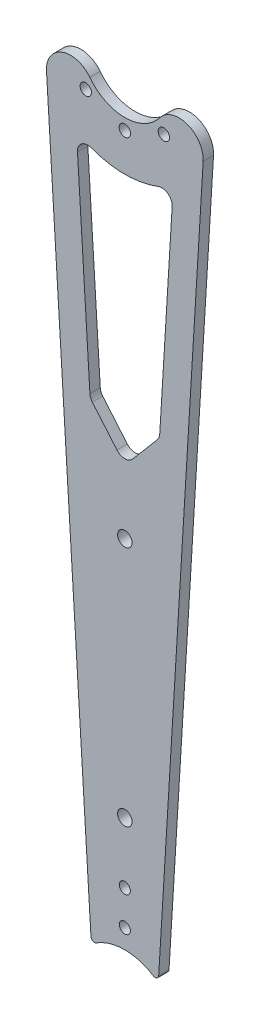
SolidWorks part; units mm, degrees
ref_plane "前视基准面" through (0, 0, 0) normal (0, 0, 1) x (1, 0, 0)
ref_plane "上视基准面" through (0, 0, 0) normal (0, 1, 0) x (1, 0, 0)
ref_plane "右视基准面" through (0, 0, 0) normal (1, 0, 0) x (0, 0, -1)
other "Configuration Table"
sketch "草图1" plane through (0, 0, 0) normal (0, 0, 1) x (1, 0, 0)
  line L0 (0, 0) -> (0, -21.9886) construction
  line L1 (0, 0) -> (-15.3152, -15.3152) construction
  line L2 (0, 0) -> (17.1443, -17.1443) construction
  line L3 (0, 50.5605) -> (0, -381.1612) construction
  line L4 (0, 0) -> (-15.4548, -4.1411) construction
  line L5 (10, -220) -> (-10, -220)
  line L6 (-10, -220) -> (-22.6976, -12.3955)
  line L8 (10, -220) -> (22.6976, -12.3955)
  circle A0 centre (0, 0) radius 16 construction
  circle A1 centre (0, 0) radius 12.75
  circle A2 centre (-11.3137, -11.3137) radius 1.65
  circle A3 centre (0, -16) radius 1.65
  circle A4 centre (11.3137, -11.3137) radius 1.65
  arc A6 (-10.1423, -7.7263) -> (-22.6976, -12.3955) centre (-15.7107, -11.9682) ccw
  arc A7 (10.1423, -7.7263) -> (22.6976, -12.3955) centre (15.7107, -11.9682) cw
  point P15 (0, -220)
  point P22 (0, -220)
  dimension "D1" = 32
  dimension "D2" = 25.5
  dimension "D5" = 3.3
  dimension "D6" = 3.3
  dimension "D7" = 3.3
  dimension "D12" = 14
  dimension "D3" = 45
  dimension "D4" = 45
  dimension "D8" = 220
  dimension "D9" = 75
  dimension "D10" = 10
  dimension "D11" = 3.5
extrude "凸台-拉伸1" add sketch "草图1" along normal blind 3
sketch "草图2" plane through (0, 0, 3) normal (0, 0, 1) x (1, 0, 0)
  line L0 (0, -227.7236) -> (0, -87.6518) construction
  line L1 (10, -220) -> (-10, -220) construction
  circle A0 centre (0, -216) radius 1.6
  circle A1 centre (0, -206) radius 1.6
  dimension "D1" = 4
  dimension "D2" = 10
  dimension "D3" = 3.2
  dimension "D4" = 3.2
extrude "切除-拉伸1" cut sketch "草图2" against normal blind 15
sketch "草图4" plane through (0, 0, 0) normal (0, 0, -1) x (-1, 0, 0)
  line L0 (-13.7159, -28.2019) -> (-10.1137, -87.0977)
  line L1 (-10, -220) -> (-22.6976, -12.3955) construction
  line L2 (0, 41.4898) -> (0, 27) construction
  line L3 (2.2925, -97.284) -> (9.4118, -88.8496)
  line L4 (0, -27) -> (0, -178.2536) construction
  line L5 (-2.2925, -97.284) -> (-9.4118, -88.8496)
  line L6 (13.7159, -28.2019) -> (10.1137, -87.0977)
  arc A0 (-9.6494, -25.2169) -> (9.6494, -25.2169) centre (0, 0) ccw
  arc A1 (13.7159, -28.2019) -> (9.6494, -25.2169) centre (10.7215, -28.0187) ccw
  arc A2 (-13.7159, -28.2019) -> (-9.6494, -25.2169) centre (-10.7215, -28.0187) cw
  arc A3 (9.4118, -88.8496) -> (10.1137, -87.0977) centre (7.1193, -86.9146) ccw
  arc A4 (2.2925, -97.284) -> (-2.2925, -97.284) centre (0, -95.349) cw
  arc A5 (-10.1137, -87.0977) -> (-9.4118, -88.8496) centre (-7.1193, -86.9146) ccw
  point P15 (14.0299, -23.0686)
  point P18 (-14.0299, -23.0686)
  point P22 (10.053, -88.09)
  point P25 (0, -100)
  point P28 (-10.053, -88.09)
  dimension "D2" = 54
  dimension "D3" = 3
  dimension "D6" = 3
  dimension "D1" = 8
  dimension "D4" = 100
  dimension "D5" = 60
extrude "切除-拉伸2" cut sketch "草图4" against normal blind 15
sketch "草图5" plane through (0, 0, 3) normal (0, 0, 1) x (1, 0, 0)
  line L0 (-12.2411, -94.7997) -> (-2.2925, -106.5861) construction
  line L1 (-9.4118, -88.8496) -> (-2.2925, -97.284) construction
  line L2 (-10, -220) -> (-22.6976, -12.3955) construction
  line L3 (-8.4988, -198.4027) -> (8.4988, -198.4027) construction
  line L4 (-17.528, -96.9179) -> (-11.4932, -195.5858) construction
  line L6 (17.528, -96.9179) -> (11.4932, -195.5858) construction
  line L7 (12.2411, -94.7997) -> (2.2925, -106.5861) construction
  line L8 (0, -107.651) -> (0, -201.1469) construction
  circle A0 centre (0, -188.4027) radius 2.1
  arc A1 (11.4932, -195.5858) -> (8.4988, -198.4027) centre (8.4988, -195.4027) cw construction
  arc A2 (-8.4988, -198.4027) -> (-11.4932, -195.5858) centre (-8.4988, -195.4027) cw construction
  arc A3 (2.2925, -106.5861) -> (-2.2925, -106.5861) centre (0, -104.651) cw construction
  arc A4 (17.528, -96.9179) -> (12.2411, -94.7997) centre (14.5336, -96.7348) ccw construction
  arc A5 (-12.2411, -94.7997) -> (-17.528, -96.9179) centre (-14.5336, -96.7348) ccw construction
  circle A6 centre (0, -118.4027) radius 2.1
  point P12 (-11.3209, -198.4027)
  point P23 (-18.0807, -87.8814)
  dimension "D2" = 3
  dimension "D3" = 4.2
  dimension "D4" = 4.2
  dimension "D5" = 10
  dimension "D6" = 70
  dimension "D1" = 6
extrude "切除-拉伸4" cut sketch "草图5" against normal blind 10
sketch "草图3" plane through (0, 0, 3) normal (0, 0, 1) x (1, 0, 0)
  line L0 (-10, -220) -> (-9.806, -223.1719)
  line L3 (0, -220) -> (0, -221.5633) construction
  line L5 (10, -220) -> (9.806, -223.1719)
  line L6 (-10, -220) -> (-22.6976, -12.3955) construction
  line L10 (-22.6976, -12.3955) -> (-10, -220)
  line L11 (-10, -220) -> (10, -220)
  line L12 (10, -220) -> (22.6976, -12.3955)
  line L13 (-22.6976, -12.3955) -> (-10, -220)
  line L14 (-10, -220) -> (10, -220)
  line L15 (10, -220) -> (22.6976, -12.3955)
  arc A0 (8.2741, -223.9564) -> (-8.2741, -223.9564) centre (0, -237.0633) ccw
  arc A1 (-9.806, -223.1719) -> (-8.2741, -223.9564) centre (-8.8079, -223.1108) ccw
  arc A2 (9.806, -223.1719) -> (8.2741, -223.9564) centre (8.8079, -223.1108) cw
  arc A6 (22.6976, -12.3955) -> (10.1423, -7.7263) centre (15.7107, -11.9682) ccw
  arc A7 (-10.1423, -7.7263) -> (10.1423, -7.7263) centre (0, 0) ccw
  arc A8 (-10.1423, -7.7263) -> (-22.6976, -12.3955) centre (-15.7107, -11.9682) ccw
  arc A9 (22.6976, -12.3955) -> (10.1423, -7.7263) centre (15.7107, -11.9682) ccw
  arc A10 (-10.1423, -7.7263) -> (10.1423, -7.7263) centre (0, 0) ccw
  arc A11 (-10.1423, -7.7263) -> (-22.6976, -12.3955) centre (-15.7107, -11.9682) ccw
  line M10 (-10, -220) -> (10, -220)
  dimension "D1" = 31
  dimension "D2" = 2
  dimension "D3" = 3.1778
  dimension "D4" = 0
extrude "凸台-拉伸2" add sketch "草图3" against normal blind 3 contours L14 L3 A0 A2 L5 | L3 L0 A1 A0 M10
sketch "草图6" plane through (0, 0, 3) normal (0, 0, 1) x (1, 0, 0)
  line L0 (-11.6446, -193.1108) -> (11.6446, -193.1108)
  line L2 (-22.6976, -12.3955) -> (-9.806, -223.1719)
  line L3 (9.806, -223.1719) -> (22.6976, -12.3955)
  line L4 (-22.6976, -12.3955) -> (-9.806, -223.1719)
  line L5 (9.806, -223.1719) -> (22.6976, -12.3955)
  circle A0 centre (0, -216) radius 1.6 construction
  circle A1 centre (0, -216) radius 1.6
  circle A2 centre (0, -206) radius 1.6 construction
  circle A3 centre (0, -206) radius 1.6
  arc A6 (22.6976, -12.3955) -> (10.1423, -7.7263) centre (15.7107, -11.9682) ccw
  arc A7 (-10.1423, -7.7263) -> (10.1423, -7.7263) centre (0, 0) ccw
  arc A8 (-10.1423, -7.7263) -> (-22.6976, -12.3955) centre (-15.7107, -11.9682) ccw
  arc A9 (-9.806, -223.1719) -> (-8.2741, -223.9564) centre (-8.8079, -223.1108) ccw
  arc A10 (8.2741, -223.9564) -> (-8.2741, -223.9564) centre (0, -237.0633) ccw
  arc A11 (8.2741, -223.9564) -> (9.806, -223.1719) centre (8.8079, -223.1108) ccw
  arc A12 (22.6976, -12.3955) -> (10.1423, -7.7263) centre (15.7107, -11.9682) ccw
  arc A13 (-10.1423, -7.7263) -> (10.1423, -7.7263) centre (0, 0) ccw
  arc A14 (-10.1423, -7.7263) -> (-22.6976, -12.3955) centre (-15.7107, -11.9682) ccw
  arc A15 (-9.806, -223.1719) -> (-8.2741, -223.9564) centre (-8.8079, -223.1108) ccw
  arc A16 (8.2741, -223.9564) -> (-8.2741, -223.9564) centre (0, -237.0633) ccw
  arc A17 (8.2741, -223.9564) -> (9.806, -223.1719) centre (8.8079, -223.1108) ccw
  dimension "D2" = 30
  dimension "D1" = 0
